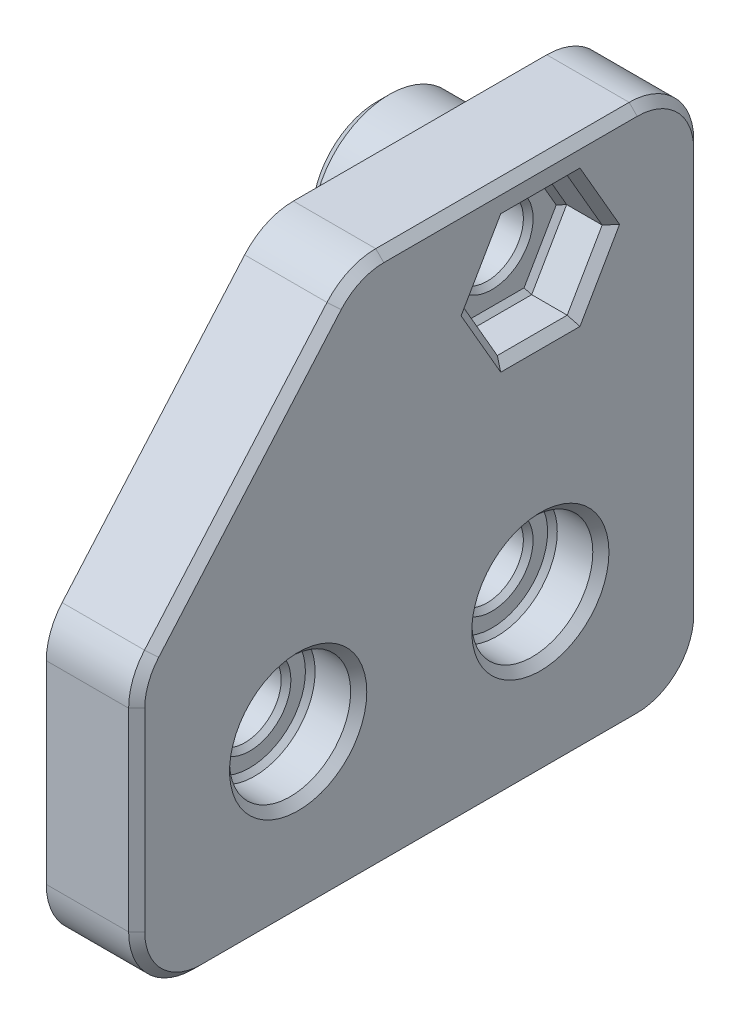
SolidWorks part; units mm, degrees
ref_plane "Front Plane" through (0, 0, 0) normal (0, 0, 1) x (1, 0, 0)
ref_plane "Top Plane" through (0, 0, 0) normal (0, 1, 0) x (1, 0, 0)
ref_plane "Right Plane" through (0, 0, 0) normal (1, 0, 0) x (0, 0, -1)
sketch "Sketch1" plane through (0, 0, 0) normal (1, 0, 0) x (0, 0, -1)
  line L0 (0, -10) -> (0, 23) construction
  line L1 (10, 0) -> (-25, 0) construction
  line L2 (-21, -10) -> (6, -10)
  line L3 (10, -6) -> (10, 19)
  line L4 (6, 23) -> (-9.6957, 23)
  line L5 (-12.7141, 21.6247) -> (-24.0184, 8.6247)
  line L6 (-25, 6) -> (-25, -6)
  line L7 (0, 17.25) -> (-15, 0) construction
  circle A0 centre (0, 0) radius 2 construction
  circle A1 centre (0, 17.25) radius 2 construction
  circle A2 centre (-15, 0) radius 2.25
  circle A3 centre (0, 17.25) radius 2.25
  circle A4 centre (0, 0) radius 2.25
  arc A5 (6, -10) -> (10, -6) centre (6, -6) ccw
  arc A6 (10, 19) -> (6, 23) centre (6, 19) ccw
  arc A7 (-9.6957, 23) -> (-12.7141, 21.6247) centre (-9.6957, 19) ccw
  arc A8 (-24.0184, 8.6247) -> (-25, 6) centre (-21, 6) ccw
  arc A9 (-25, -6) -> (-21, -10) centre (-21, -6) ccw
  point P30 (-25, 0)
  dimension "D2" = 4
  dimension "D3" = 4
  dimension "D10" = 4
  dimension "D5" = 15
  dimension "D6" = 17.25
  dimension "D7" = 10
  dimension "D8" = 10
  dimension "D9" = 5.75
  dimension "D11" = 10
  dimension "D1" = 0.25
  dimension "D4" = 0.25
extrude "Boss-Extrude1" add sketch "Sketch1" along normal blind 2.6
sketch "Sketch2" plane through (0, 0, 0) normal (-1, 0, 0) x (0, 0, 1)
  circle A0 centre (0, 17.25) radius 2.25 construction
  circle A1 centre (0, 17.25) radius 2.25 construction
  circle A2 centre (0, 17.25) radius 2.5
  circle A3 centre (0, 17.25) radius 5 construction
  circle A4 centre (0, 17.25) radius 4.75
  dimension "D1" = 0.25
  dimension "D2" = 10
  dimension "D3" = 0.25
extrude "Boss-Extrude2" add sketch "Sketch2" along normal blind 4.5
chamfer "Chamfer1" distance 0.75 angle 45 1 edges at (-4.5, 17.25, 4.75)
sketch "Sketch3" plane through (2.6, 0, 0) normal (1, 0, 0) x (0, 0, -1)
  line L0 (2.1651, 21) -> (-2.1651, 21)
  line L1 (2.0207, 20.75) -> (-2.0207, 20.75) construction
  line L2 (-2.0207, 20.75) -> (-4.0415, 17.25) construction
  line L3 (-4.0415, 17.25) -> (-2.0207, 13.75) construction
  line L4 (-2.0207, 13.75) -> (2.0207, 13.75) construction
  line L5 (-21, -10) -> (6, -10)
  line L6 (10, -6) -> (10, 19)
  line L7 (6, 23) -> (-9.6957, 23)
  line L8 (-12.7141, 21.6247) -> (-24.0184, 8.6247)
  line L9 (-25, 6) -> (-25, -6)
  line L10 (-21, -10) -> (6, -10)
  line L11 (10, -6) -> (10, 19)
  line L12 (6, 23) -> (-9.6957, 23)
  line L13 (-12.7141, 21.6247) -> (-24.0184, 8.6247)
  line L14 (-25, 6) -> (-25, -6)
  line L15 (2.0207, 13.75) -> (4.0415, 17.25) construction
  line L16 (4.0415, 17.25) -> (2.0207, 20.75) construction
  line L17 (-2.1651, 21) -> (-4.3301, 17.25)
  line L18 (-4.3301, 17.25) -> (-2.1651, 13.5)
  line L19 (-2.1651, 13.5) -> (2.1651, 13.5)
  line L20 (2.1651, 13.5) -> (4.3301, 17.25)
  line L21 (4.3301, 17.25) -> (2.1651, 21)
  circle A0 centre (0, 0) radius 3.5 construction
  circle A1 centre (-15, 0) radius 3.75
  circle A2 centre (-15, 0) radius 2.25 construction
  circle A3 centre (0, 0) radius 2.25 construction
  circle A4 centre (0, 0) radius 3.75
  arc A5 (-25, -6) -> (-21, -10) centre (-21, -6) ccw
  arc A6 (6, -10) -> (10, -6) centre (6, -6) ccw
  arc A7 (10, 19) -> (6, 23) centre (6, 19) ccw
  arc A8 (-9.6957, 23) -> (-12.7141, 21.6247) centre (-9.6957, 19) ccw
  arc A9 (-24.0184, 8.6247) -> (-25, 6) centre (-21, 6) ccw
  arc A10 (-25, -6) -> (-21, -10) centre (-21, -6) ccw
  arc A11 (6, -10) -> (10, -6) centre (6, -6) ccw
  arc A12 (10, 19) -> (6, 23) centre (6, 19) ccw
  arc A13 (-9.6957, 23) -> (-12.7141, 21.6247) centre (-9.6957, 19) ccw
  arc A14 (-24.0184, 8.6247) -> (-25, 6) centre (-21, 6) ccw
  circle A15 centre (0, 17.25) radius 3.5 construction
  circle A16 centre (0, 17.25) radius 2.25 construction
  dimension "D3" = 0.25
  dimension "D2" = 7
  dimension "D4" = 7
  dimension "D5" = 0.25
extrude "Boss-Extrude3" add sketch "Sketch3" along normal blind 3
chamfer "Chamfer2" distance 0.3 angle 45 11 edges at (2.6, 0, 11.25) (2.6, 0, 12.75) (2.6, 0, -3.75) (2.6, 0, -2.25) (2.6, 13.5, 0) (2.6, 15.375, 3.2476) (2.6, 19.125, 3.2476) (2.6, 21, 0) (2.6, 19.125, -3.2476) (2.6, 15.375, -3.2476) (2.6, 17.25, -2.25)
chamfer "Chamfer3" distance 0.5 angle 45 18 edges at (5.6, 19.125, 3.2476) (5.6, 15.375, 3.2476) (5.6, 13.5, 0) (5.6, 15.375, -3.2476) (5.6, 19.125, -3.2476) (5.6, 21, 0) (5.6, 0, -3.75) (5.6, 0, 25) (5.6, 7.4011, 24.7466) (5.6, 15.1247, 18.3662) (5.6, 22.64, 11.3541) (5.6, 23, 1.8478) (5.6, 21.8284, -8.8284) (5.6, 6.5, -10) (5.6, -8.8284, -8.8284) (5.6, -10, 7.5) (5.6, -8.8284, 23.8284) (5.6, 0, 11.25)
equation "\"Tolerance\" = 0.25mm"
equation "\"D1@Sketch1\"=\"Tolerance\""
equation "\"D4@Sketch1\"=\"Tolerance\""
equation "\"D1@Sketch2\"=\"Tolerance\""
equation "\"D3@Sketch2\"=\"Tolerance\""
equation "\"Pocket_Head_M5\"= 8mm"
equation "\"Pocket_Head_M4\" = 7mm"
equation "\"D2@Sketch3\"=\"Pocket_Head_M4\""
equation "\"D3@Sketch3\"=\"Tolerance\""
equation "\"Pocket_Nut_M4\" = 7mm"
equation "\"D4@Sketch3\"=\"Pocket_Nut_M4\""
equation "\"D5@Sketch3\"=\"Tolerance\""
